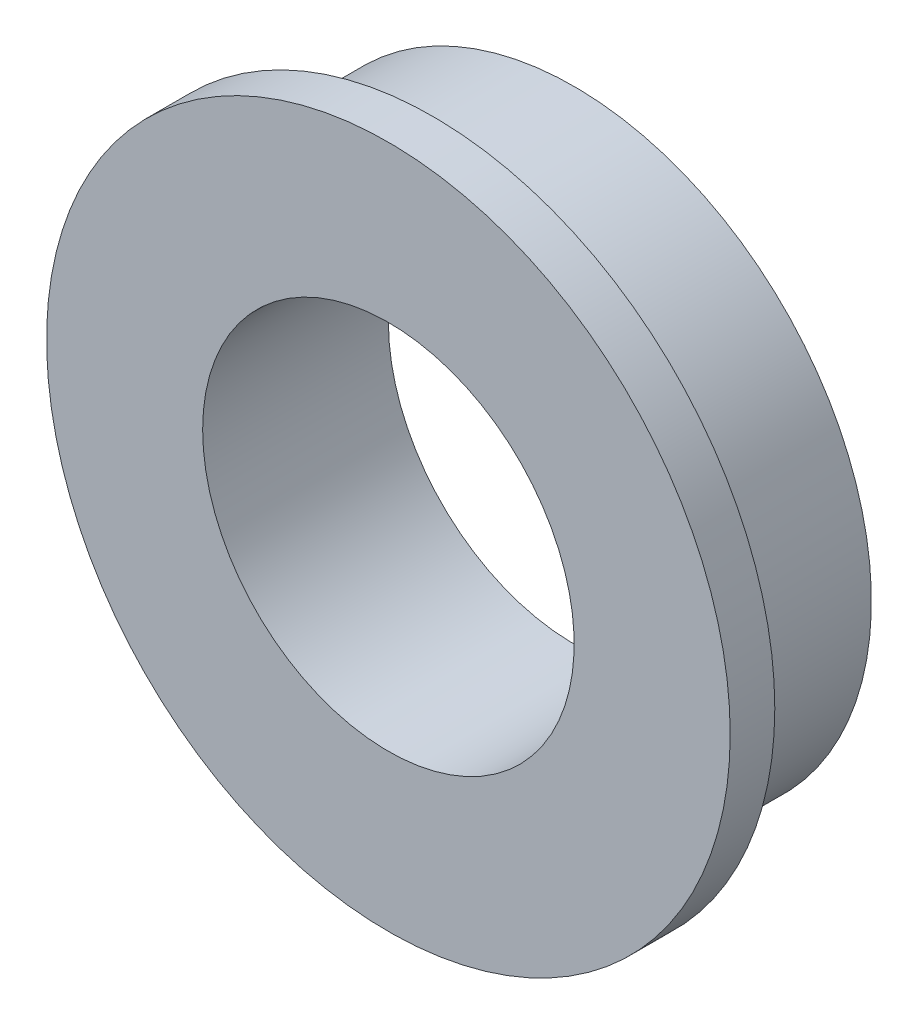
SolidWorks part; units mm, degrees
ref_plane "前视基准面" through (0, 0, 0) normal (0, 0, 1) x (1, 0, 0)
ref_plane "上视基准面" through (0, 0, 0) normal (0, 1, 0) x (1, 0, 0)
ref_plane "右视基准面" through (0, 0, 0) normal (1, 0, 0) x (0, 0, -1)
sketch "草图1" plane through (0, 0, 0) normal (0, 0, 1) x (1, 0, 0)
  circle A0 centre (0, 0) radius 4
  circle A1 centre (0, 0) radius 2.5
  dimension "D1" = 8
  dimension "D2" = 5
extrude "凸台-拉伸1" add sketch "草图1" along normal blind 1.9
sketch "草图2" plane through (0, 0, 1.9) normal (0, 0, 1) x (1, 0, 0)
  circle A0 centre (0, 0) radius 2.5
  circle A1 centre (0, 0) radius 4.6
  dimension "D1" = 9.2
  dimension "D2" = 5
extrude "凸台-拉伸2" add sketch "草图2" along normal blind 0.6
